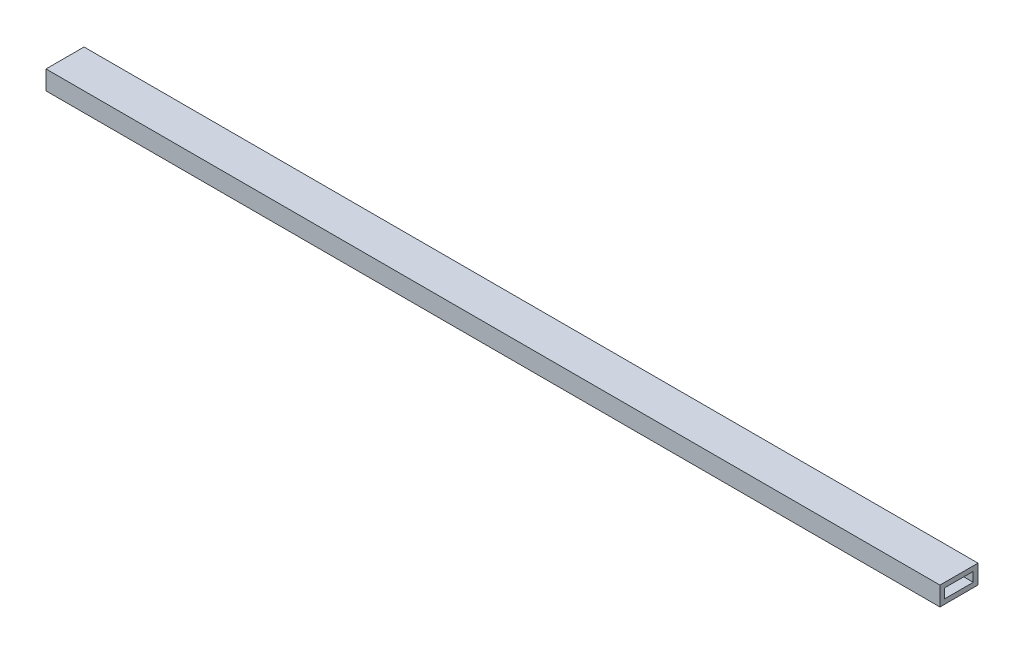
SolidWorks part; units mm, degrees
ref_plane "Front Plane" through (0, 0, 0) normal (0, 0, 1) x (1, 0, 0)
ref_plane "Top Plane" through (0, 0, 0) normal (0, 1, 0) x (1, 0, 0)
ref_plane "Right Plane" through (0, 0, 0) normal (1, 0, 0) x (0, 0, -1)
sketch "Sketch1" plane through (0, 0, 0) normal (1, 0, 0) x (0, 0, -1)
  line L1 (0, 0) -> (25.4, 0)
  line L2 (0, 0) -> (0, 12.7)
  line L3 (0, 12.7) -> (25.4, 12.7)
  line L4 (25.4, 0) -> (25.4, 12.7)
  dimension "D1" = 12.7
  dimension "D2" = 25.4
extrude "Extrude-Thin1" add sketch "Sketch1" along normal blind 596.9 thin thin type one direction reverse wall 3.175
